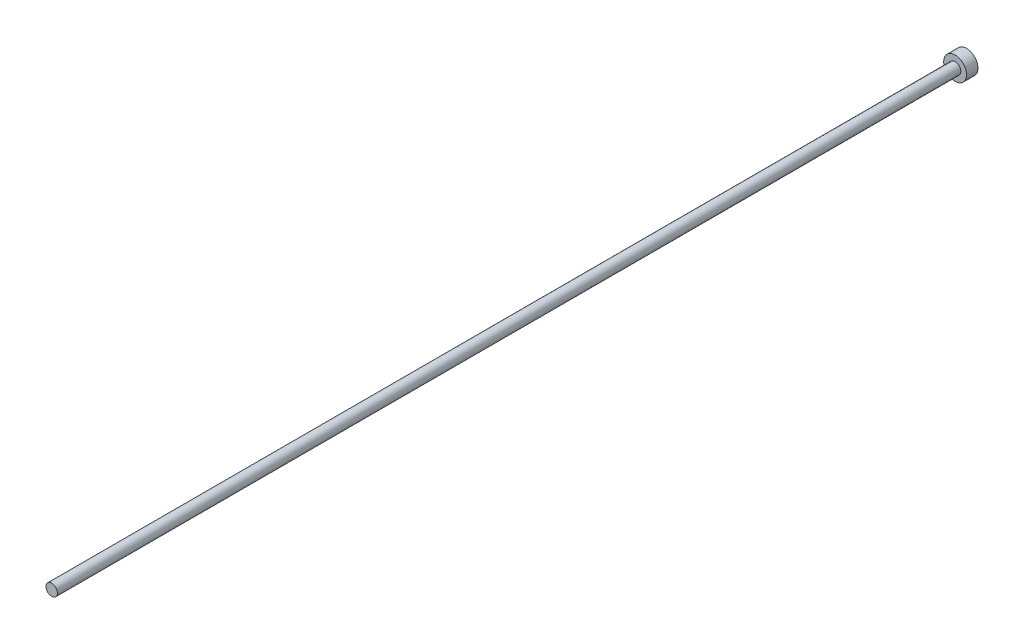
SolidWorks part; units mm, degrees
ref_plane "Front Plane" through (0, 0, 0) normal (0, 0, 1) x (1, 0, 0)
ref_plane "Top Plane" through (0, 0, 0) normal (0, 1, 0) x (1, 0, 0)
ref_plane "Right Plane" through (0, 0, 0) normal (1, 0, 0) x (0, 0, -1)
sketch "Sketch1" plane through (0, 0, 0) normal (1, 0, 0) x (0, 0, -1)
  line L0 (-80, 0) -> (80, 0) construction
  line L1 (80, 2) -> (80, -2) construction
  line L2 (80, 2) -> (78, 2) construction
  line L3 (-80, -1) -> (-80, 1) construction
  point P7 (-80, 0)
  dimension "Length" = 160
  dimension "Head Height" = 2
  dimension "Head Diameter" = 4
  dimension "Diameter" = 2
sketch "Sketch2" plane through (0, 0, 0) normal (1, 0, 0) x (0, 0, -1)
  line L0 (80, 0) -> (80, 2)
  line L1 (80, 2) -> (78, 2)
  line L2 (78, 2) -> (78, 1)
  line L3 (78, 1) -> (-80, 1)
  line L4 (-80, 1) -> (-80, 0)
  line L5 (-80, 0) -> (80, 0)
revolve "Revolve1" add sketch "Sketch2" angle 360 about L0
